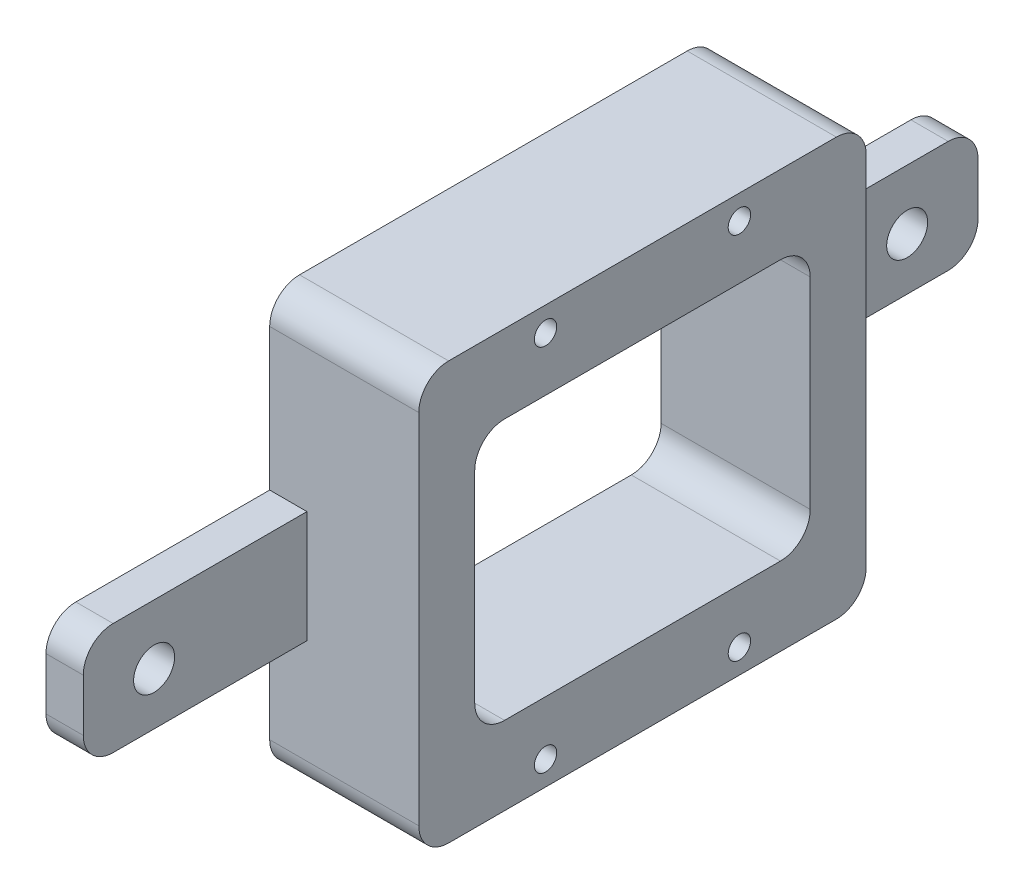
SolidWorks part; units mm, degrees
ref_plane "前视基准面" through (0, 0, 0) normal (0, 0, 1) x (1, 0, 0)
ref_plane "上视基准面" through (0, 0, 0) normal (0, 1, 0) x (1, 0, 0)
ref_plane "右视基准面" through (0, 0, 0) normal (1, 0, 0) x (0, 0, -1)
other "Configuration Table"
sketch "草图1" plane through (0, 0, 0) normal (1, 0, 0) x (0, 0, -1)
  line L1 (-30, 28) -> (30, 28)
  line L2 (-30, 28) -> (-30, -28)
  line L3 (-30, -28) -> (30, -28)
  line L4 (30, 28) -> (30, -28)
  dimension "D1" = 60
  dimension "D2" = 56
  dimension "D3" = 30
  dimension "D4" = 28
extrude "凸台-拉伸1" add sketch "草图1" along normal blind 20
sketch "草图6" plane through (20, 0, 0) normal (1, 0, 0) x (0, 0, -1)
  line L0 (30, -28) -> (30, 28) construction
  line L1 (30, 5) -> (60, 5)
  line L2 (30, 5) -> (30, -10)
  line L3 (30, -10) -> (60, -10)
  line L4 (60, 5) -> (60, -10)
  line L6 (-30, -10) -> (-60, -10)
  line L7 (-30, -10) -> (-30, 5)
  line L8 (-30, 5) -> (-60, 5)
  line L9 (-60, -10) -> (-60, 5)
  line L10 (-30, 28) -> (-30, -28) construction
  dimension "D1" = 30
  dimension "D2" = 30
  dimension "D3" = 15
  dimension "D4" = 10
extrude "凸台-拉伸3" add sketch "草图6" against normal blind 5 from offset 15 offset against normal yes
sketch "草图7" plane through (20, 0, 0) normal (1, 0, 0) x (0, 0, -1)
  line L1 (-13, 24.75) -> (13, 24.75) construction
  line L2 (-13, 24.75) -> (-13, -24.75) construction
  line L3 (-13, -24.75) -> (13, -24.75) construction
  line L4 (13, 24.75) -> (13, -24.75) construction
  circle A0 centre (-13, 24.75) radius 1.5
  circle A1 centre (13, 24.75) radius 1.5
  circle A2 centre (13, -24.75) radius 1.5
  circle A3 centre (-13, -24.75) radius 1.5
  dimension "D5" = 3
  dimension "D1" = 26
  dimension "D2" = 49.5
  dimension "D3" = 13
  dimension "D4" = 24.75
extrude "切除-拉伸2" cut sketch "草图7" against normal through all
sketch "草图8" plane through (20, 0, 0) normal (1, 0, 0) x (0, 0, -1)
  circle A0 centre (-50.5, -3) radius 2.75
  circle A1 centre (50.5, -3) radius 2.75
  point P4 (0, 0)
  dimension "D1" = 101
  dimension "D3" = 5.5
  dimension "D2" = 50.5
  dimension "D4" = 3
extrude "切除-拉伸3" cut sketch "草图8" against normal blind 5 from offset 15 offset against normal yes
fillet "圆角2" radius 4 8 edges at (2.5, 5, 60) (10, 28, 30) (10, 28, -30) (2.5, 5, -60) (2.5, -10, -60) (10, -28, -30) (10, -28, 30) (2.5, -10, 60)
sketch "草图9" plane through (20, 0, 0) normal (1, 0, 0) x (0, 0, -1)
  line L1 (-22.5, 17.5) -> (22.5, 17.5)
  line L2 (-22.5, 17.5) -> (-22.5, -17.5)
  line L3 (-22.5, -17.5) -> (22.5, -17.5)
  line L4 (22.5, 17.5) -> (22.5, -17.5)
  dimension "D1" = 45
  dimension "D2" = 35
  dimension "D3" = 17.5
  dimension "D4" = 22.5
extrude "切除-拉伸4" cut sketch "草图9" against normal through all
fillet "圆角3" radius 4 4 edges at (10, -17.5, -22.5) (10, -17.5, 22.5) (10, 17.5, 22.5) (10, 17.5, -22.5)
